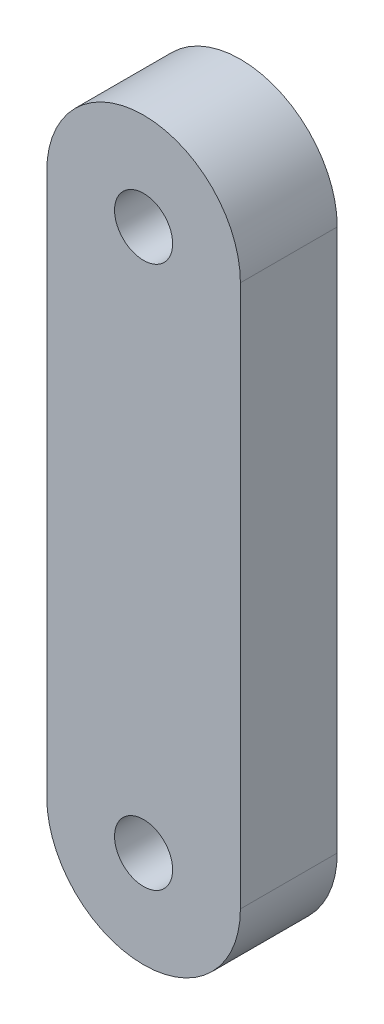
SolidWorks part; units mm, degrees
ref_plane "Front Plane" through (0, 0, 0) normal (0, 0, 1) x (1, 0, 0)
ref_plane "Top Plane" through (0, 0, 0) normal (0, 1, 0) x (1, 0, 0)
ref_plane "Right Plane" through (0, 0, 0) normal (1, 0, 0) x (0, 0, -1)
sketch "Sketch1" plane through (0, 0, 0) normal (0, 0, 1) x (1, 0, 0)
  line L0 (0, 0) -> (0, 28) construction
  line L1 (-5, 0) -> (-5, 28)
  line L2 (5, 0) -> (5, 28)
  arc A0 (-5, 0) -> (5, 0) centre (0, 0) ccw
  arc A1 (5, 28) -> (-5, 28) centre (0, 28) ccw
  circle A2 centre (0, 0) radius 1.5
  circle A3 centre (0, 28) radius 1.5
  point P3 (0, 14)
  dimension "D1" = 5
  dimension "D3" = 3
  dimension "D2" = 28
extrude "Boss-Extrude1" add sketch "Sketch1" along normal blind 5
